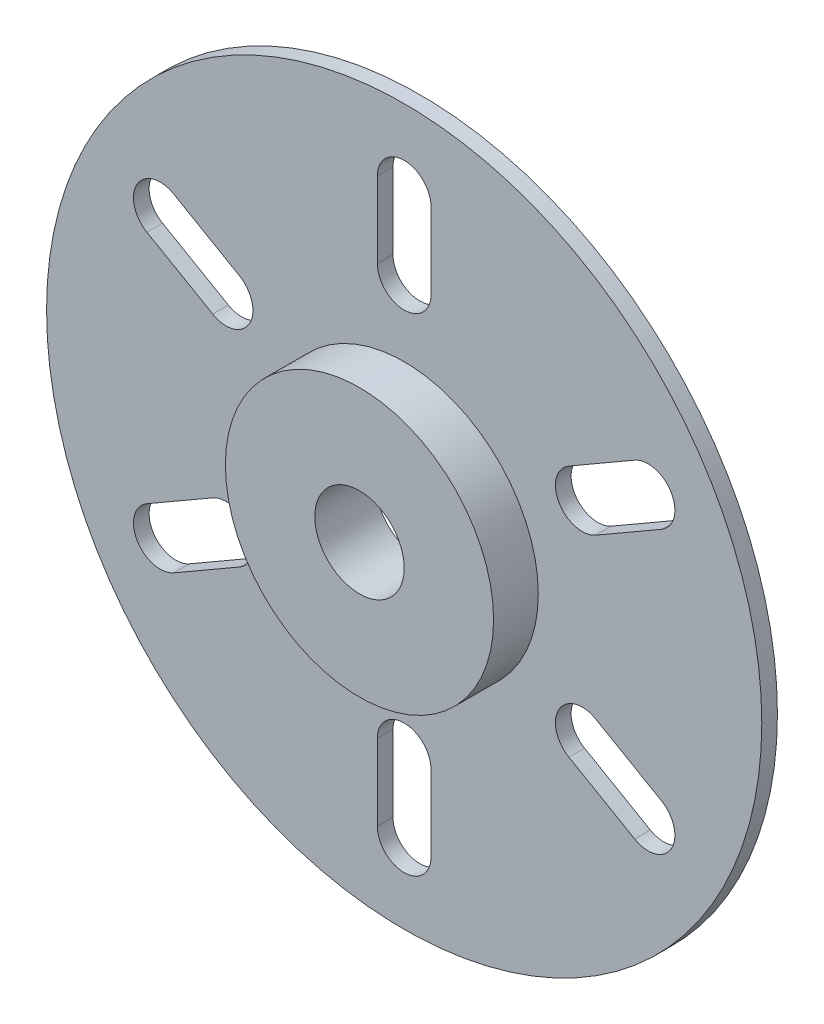
SolidWorks part; units mm, degrees
ref_plane "Front Plane" through (0, 0, 0) normal (0, 0, 1) x (1, 0, 0)
ref_plane "Top Plane" through (0, 0, 0) normal (0, 1, 0) x (1, 0, 0)
ref_plane "Right Plane" through (0, 0, 0) normal (1, 0, 0) x (0, 0, -1)
sketch "Sketch1" plane through (0, 0, 0) normal (0, 0, 1) x (1, 0, 0)
  circle A0 centre (0, 0) radius 80
  dimension "D1" = 160
extrude "Boss-Extrude1" add sketch "Sketch1" along normal blind 3.5
sketch "Sketch2" plane through (0, 0, 3.5) normal (0, 0, 1) x (1, 0, 0)
  circle A0 centre (0, 0) radius 10
  dimension "D1" = 20
extrude "Cut-Extrude1" cut sketch "Sketch2" against normal blind 3.5
sketch "Sketch3" plane through (0, 0, 3.5) normal (0, 0, 1) x (1, 0, 0)
  circle A0 centre (0, 0) radius 30
  circle A1 centre (0, 0) radius 10
  dimension "D1" = 20
extrude "Boss-Extrude2" add sketch "Sketch3" along normal blind 10
sketch "Sketch6" plane through (0, 0, 3.5) normal (0, 0, 1) x (1, 0, 0)
  line L13 (39.8372, 23) -> (54.5596, 31.5) construction
  line L14 (36.8372, 28.1962) -> (51.5596, 36.6962)
  line L15 (42.8372, 17.8038) -> (57.5596, 26.3038)
  line L16 (39.8372, -23) -> (54.5596, -31.5) construction
  line L17 (42.8372, -17.8038) -> (57.5596, -26.3038)
  line L18 (36.8372, -28.1962) -> (51.5596, -36.6962)
  line L19 (0, -46) -> (0, -63) construction
  line L20 (6, -46) -> (6, -63)
  line L21 (-6, -46) -> (-6, -63)
  line L22 (-39.8372, -23) -> (-54.5596, -31.5) construction
  line L23 (-36.8372, -28.1962) -> (-51.5596, -36.6962)
  line L24 (-42.8372, -17.8038) -> (-57.5596, -26.3038)
  line L25 (-39.8372, 23) -> (-54.5596, 31.5) construction
  line L26 (-42.8372, 17.8038) -> (-57.5596, 26.3038)
  line L27 (-36.8372, 28.1962) -> (-51.5596, 36.6962)
  line L28 (0, 46) -> (0, 63) construction
  line L34 (-6, 46) -> (-6, 63)
  line L35 (6, 46) -> (6, 63)
  arc A1 (36.8372, 28.1962) -> (42.8372, 17.8038) centre (39.8372, 23) ccw
  arc A2 (57.5596, 26.3038) -> (51.5596, 36.6962) centre (54.5596, 31.5) ccw
  arc A3 (42.8372, -17.8038) -> (36.8372, -28.1962) centre (39.8372, -23) ccw
  arc A4 (51.5596, -36.6962) -> (57.5596, -26.3038) centre (54.5596, -31.5) ccw
  arc A5 (6, -46) -> (-6, -46) centre (0, -46) ccw
  arc A6 (-6, -63) -> (6, -63) centre (0, -63) ccw
  arc A7 (-36.8372, -28.1962) -> (-42.8372, -17.8038) centre (-39.8372, -23) ccw
  arc A8 (-57.5596, -26.3038) -> (-51.5596, -36.6962) centre (-54.5596, -31.5) ccw
  arc A9 (-42.8372, 17.8038) -> (-36.8372, 28.1962) centre (-39.8372, 23) ccw
  arc A10 (-51.5596, 36.6962) -> (-57.5596, 26.3038) centre (-54.5596, 31.5) ccw
  arc A16 (-6, 46) -> (6, 46) centre (0, 46) ccw
  arc A17 (6, 63) -> (-6, 63) centre (0, 63) ccw
  point P14 (47.1984, 27.25)
  point P19 (47.1984, -27.25)
  point P26 (0, -54.5)
  point P33 (-47.1984, -27.25)
  point P40 (-47.1984, 27.25)
  point P49 (0, 54.5)
  dimension "D6" = 6
  dimension "D7" = 6
  dimension "D8" = 6
  dimension "D9" = 6
  dimension "D10" = 6
  dimension "D12" = 6
  dimension "D17" = 17
  dimension "D18" = 17
  dimension "D19" = 17
  dimension "D20" = 17
  dimension "D21" = 17
  dimension "D22" = 17
extrude "Cut-Extrude2" cut sketch "Sketch6" against normal blind 3.5
